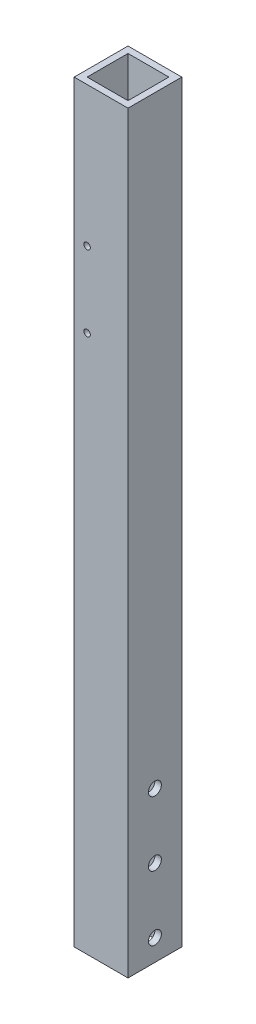
SolidWorks part; units mm, degrees
ref_plane "前视基准面" through (0, 0, 0) normal (0, 0, 1) x (1, 0, 0)
ref_plane "上视基准面" through (0, 0, 0) normal (0, 1, 0) x (1, 0, 0)
ref_plane "右视基准面" through (0, 0, 0) normal (1, 0, 0) x (0, 0, -1)
other "Configuration Table"
sketch "草图1" plane through (0, 0, 0) normal (0, 1, 0) x (1, 0, 0)
  line L1 (0, 0) -> (25, 0)
  line L2 (0, 0) -> (0, 25)
  line L3 (0, 25) -> (25, 25)
  line L4 (25, 0) -> (25, 25)
  line L5 (3, 3) -> (22, 3)
  line L6 (3, 3) -> (3, 22)
  line L7 (3, 22) -> (22, 22)
  line L8 (22, 3) -> (22, 22)
  dimension "D1" = 25
  dimension "D2" = 25
  dimension "D3" = 3
  dimension "D4" = 3
  dimension "D5" = 3
  dimension "D6" = 3
extrude "凸台-拉伸1" add sketch "草图1" along normal blind 350
sketch "草图2" plane through (0, 0, 0) normal (1, 0, 0) x (0, 0, -1)
  line L0 (12.5, -31.3312) -> (12.5, 287.2487) construction
  line L1 (12.5, 10) -> (12.5, 40) construction
  circle A0 centre (12.5, 10) radius 3
  circle A2 centre (12.5, 40) radius 3
  circle A3 centre (12.5, 70) radius 3
  dimension "D2" = 6
  dimension "D3" = 3
  dimension "D1" = 12.5
  dimension "D4" = 10
  dimension "D5" = 30
extrude "切除-拉伸1" cut sketch "草图2" along normal through all
sketch "草图3" plane through (0, 0, 0) normal (0, 0, 1) x (1, 0, 0)
  line L0 (6, -7.4812) -> (6, 258.86) construction
  line L1 (6, 250) -> (6, 285) construction
  circle A0 centre (6, 250) radius 1.5
  circle A1 centre (6, 285) radius 1.5
  dimension "D2" = 3
  dimension "D1" = 6
  dimension "D4" = 250
  dimension "D5" = 35
  dimension "D3" = 2
extrude "切除-拉伸2" cut sketch "草图3" against normal through all both
